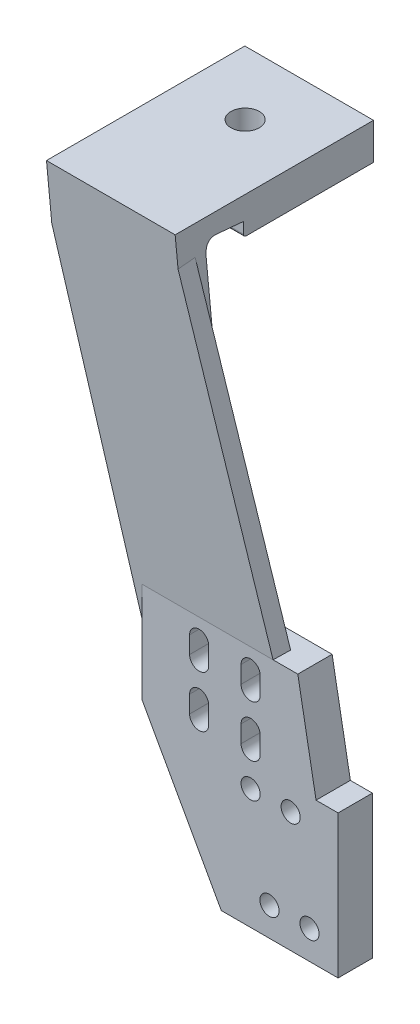
SolidWorks part; units mm, degrees
ref_plane "Front Plane" through (0, 0, 0) normal (0, 0, 1) x (1, 0, 0)
ref_plane "Top Plane" through (0, 0, 0) normal (0, 1, 0) x (1, 0, 0)
ref_plane "Right Plane" through (0, 0, 0) normal (1, 0, 0) x (0, 0, -1)
sketch "Sketch1" plane through (0, 0, 0) normal (0, 0, 1) x (1, 0, 0)
  line L0 (0, 0) -> (-40.8425, 0)
  line L5 (0, 85) -> (0, 0)
  line L6 (-40.8425, 0) -> (-68.59, 50)
  line L7 (-68.59, 50) -> (-68.59, 85)
  line L8 (-68.59, 85) -> (0, 85)
  line L9 (-30.59, 57) -> (-48.59, 57) construction
  line L10 (-48.59, 57) -> (-48.59, 75) construction
  line L11 (-48.59, 75) -> (-30.59, 75) construction
  line L12 (-30.59, 75) -> (-30.59, 57) construction
  line L13 (-30.59, 57) -> (-30.59, 42) construction
  line L14 (-30.59, 42) -> (-16.59, 42) construction
  line L15 (-16.59, 42) -> (-10, 10) construction
  line L16 (-10, 10) -> (-24, 10) construction
  line L17 (-24, 10) -> (-30.59, 42) construction
  line L18 (-48.59, 60) -> (-48.59, 54) construction
  line L19 (-45.24, 60) -> (-45.24, 54)
  line L20 (-51.94, 60) -> (-51.94, 54)
  line L21 (-48.59, 78) -> (-48.59, 72) construction
  line L22 (-45.24, 78) -> (-45.24, 72)
  line L23 (-51.94, 78) -> (-51.94, 72)
  line L24 (-30.59, 78) -> (-30.59, 72) construction
  line L25 (-27.24, 78) -> (-27.24, 72)
  line L26 (-33.94, 78) -> (-33.94, 72)
  line L27 (-30.59, 60) -> (-30.59, 54) construction
  line L28 (-27.24, 60) -> (-27.24, 54)
  line L29 (-33.94, 60) -> (-33.94, 54)
  line L30 (-33.94, 72) -> (-33.94, 60) construction
  line L31 (-30.59, 60) -> (-48.59, 60) construction
  line L32 (-45.24, 72) -> (-45.24, 60) construction
  line L33 (-48.59, 63.35) -> (-30.59, 63.35) construction
  line L34 (-48.59, 68.65) -> (-30.59, 68.65) construction
  circle A0 centre (-30.59, 42) radius 3.35
  circle A1 centre (-16.59, 42) radius 3.35
  circle A2 centre (-24, 10) radius 3.35
  circle A3 centre (-10, 10) radius 3.35
  arc A4 (-45.24, 60) -> (-51.94, 60) centre (-48.59, 60) ccw
  arc A5 (-51.94, 54) -> (-45.24, 54) centre (-48.59, 54) ccw
  arc A6 (-45.24, 78) -> (-51.94, 78) centre (-48.59, 78) ccw
  arc A7 (-51.94, 72) -> (-45.24, 72) centre (-48.59, 72) ccw
  arc A8 (-27.24, 78) -> (-33.94, 78) centre (-30.59, 78) ccw
  arc A9 (-33.94, 72) -> (-27.24, 72) centre (-30.59, 72) ccw
  arc A10 (-27.24, 60) -> (-33.94, 60) centre (-30.59, 60) ccw
  arc A11 (-33.94, 54) -> (-27.24, 54) centre (-30.59, 54) ccw
  point P20 (-48.59, 57)
  point P26 (-48.59, 75)
  point P33 (-30.59, 75)
  point P40 (-30.59, 57)
  point P54 (-78.59, 26.8043)
  point P57 (0, 0)
  point P58 (-78.59, 29.2773)
  point P59 (-63.59, 50.341)
  dimension "D10" = 6.7
  dimension "D11" = 6.7
  dimension "D12" = 6.7
  dimension "D13" = 6.7
  dimension "D14" = 3.35
  dimension "D15" = 6
  dimension "D16" = 6
  dimension "D17" = 20
  dimension "D1" = 18
  dimension "D2" = 18
  dimension "D3" = 15
  dimension "D4" = 32
  dimension "D5" = 14
  dimension "D6" = 6.59
  dimension "D7" = 10
  dimension "D8" = 10
  dimension "D9" = 85
  dimension "D18" = 50
extrude "Boss-Extrude1" add sketch "Sketch1" along normal blind 12
sketch "Sketch4" plane through (-68.59, 0, 0) normal (-1, 0, 0) x (0, 0, 1)
  line L0 (11.2201, 191.4749) -> (11.5777, 192.6361) construction
  line L1 (12.1758, 191.1806) -> (12.5792, 192.4904) construction
  line L2 (11.847, 188.2578) -> (5.8724, 123.7613) construction
  line L3 (12.5541, 195.0368) -> (12.5465, 195.8087) construction
  line L4 (12.5541, 195.0368) -> (12.5246, 198.0227) construction
  line L5 (1.3504, 200.2894) -> (-0.4753, 200.0947)
  line L6 (3.8584, 112.8614) -> (0, 71.2101) construction
  line L7 (10.8512, 188.3501) -> (4.8766, 123.8536) construction
  line L9 (0, 85) -> (0, 50) construction
  line L10 (5.8724, 123.7613) -> (2.2817, 85)
  line L11 (0, 85) -> (0, 71.2101) construction
  line L20 (12.5465, 195.8087) -> (5.8724, 123.7613)
  line L21 (4.8541, 112.7691) -> (0, 60.3688) construction
  line L22 (-0.4753, 200.0947) -> (-0.4753, 198.17)
  line L23 (-45.9753, 195.2536) -> (-45.9753, 208.0041)
  line L24 (-45.9753, 208.0041) -> (23.3945, 208.0041)
  line L25 (23.3945, 208.0041) -> (12, 85)
  line L26 (12, 85) -> (12, 50) construction
  line L27 (12, 85) -> (2.2817, 85)
  line L28 (9.3505, 199.9855) -> (1.4375, 199.2932) construction
  line L29 (11.5541, 195.027) -> (11.5247, 198.0128) construction
  line L30 (11.5777, 192.6361) -> (11.5541, 195.027) construction
  line L31 (-30.5003, 194.2536) -> (-16.9503, 194.2536) construction
  line L32 (-45.9753, 194.2536) -> (-1.4753, 194.2536) construction
  line L33 (0.5247, 198.17) -> (0.5247, 196.2536) construction
  line L34 (-0.4753, 198.17) -> (-0.4753, 196.2536)
  line L35 (-45.9753, 195.2536) -> (-1.4753, 195.2536)
  line L36 (2.2817, 85) -> (0, 60.3688) construction
  line L37 (12.5465, 195.8087) -> (12.5246, 198.0227)
  line L38 (9.2633, 200.9817) -> (1.3504, 200.2894)
  line L39 (12.5792, 192.4904) -> (12.5541, 195.0368) construction
  line L40 (0, 71.2101) -> (0, 60.3688) construction
  line L41 (0, 60.3688) -> (0, 50) construction
  line L42 (0, 71.2101) -> (-0.9957, 60.461) construction
  line L43 (3.8584, 112.8614) -> (-0.9957, 60.461) construction
  spline S5 degree 3 poles (9.3505, 199.9855) (10.5905, 200.094) (11.5124, 199.2576) (11.5247, 198.0128) knots 0 0 0 0 1 1 1 1 weights 1 0.786145 0.786145 1 construction
  spline S6 degree 3 poles (11.2201, 191.4749) (11.3469, 191.6574) (11.435, 191.8468) (11.5226, 192.1387) (11.5442, 192.2377) (11.5722, 192.4366) (11.5787, 192.5373) (11.5777, 192.6361) knots 0 0 0 0 0.5 0.5 0.75 0.75 1 1 1 1 construction
  spline S7 degree 3 poles (11.2201, 191.4749) (11.1122, 191.3196) (10.9929, 191.1932) (10.7375, 190.9784) (10.6, 190.89) (10.1735, 190.681) (9.8712, 190.6116) (9.5474, 190.6166) knots 0 0 0 0 0.25 0.25 0.5 0.5 1 1 1 1 construction
  spline S8 degree 3 poles (0.5247, 196.2536) (0.5247, 195.082) (-0.3038, 194.2536) (-1.4753, 194.2536) knots 0 0 0 0 1 1 1 1 weights 1 0.804738 0.804738 1 construction
  spline S9 degree 3 poles (0.5247, 198.297) (0.5247, 198.843) (0.8936, 199.2456) (1.4375, 199.2932) knots 0 0 0 0 1 1 1 1 weights 1 0.824852 0.824852 1 construction
  spline S10 degree 1 poles (-0.4753, 196.2536) (-1.4753, 195.2536) knots 0 0 1 1 construction
  spline S11 degree 3 poles (-0.4753, 196.2536) (-0.4753, 196.1287) (-0.5183, 195.8844) (-0.7462, 195.5245) (-1.1062, 195.2966) (-1.3504, 195.2536) (-1.4753, 195.2536) knots 0 0 0 0 0.25 0.5 0.75 1 1 1 1
  spline S13 degree 1 poles (9.2633, 200.9817) (12.5246, 198.0227) knots 0 0 1 1 construction
  spline S15 degree 3 poles (12.5246, 198.0227) (12.5228, 198.213) (12.4851, 198.5848) (12.2469, 199.3733) (11.6072, 200.2883) (10.6345, 200.8363) (9.8266, 200.9968) (9.4529, 200.9983) (9.2633, 200.9817) knots 0 0 0 0 0.125 0.25 0.5 0.75 0.875 1 1 1 1
  dimension "D1" = 1
  dimension "D4" = 12.7505
  dimension "D5" = 45.5
  dimension "D2" = 1
  dimension "D3" = 1
extrude "Boss-Extrude4" add sketch "Sketch4" against normal blind 23
sketch "Sketch6" plane through (0, 0, 12) normal (0, 0, 1) x (1, 0, 0)
  line L1 (33.593, 50) -> (-42.0441, 50) construction
  line L3 (-66.4213, 50.1) -> (-8.9266, 50.1) construction
  line L4 (-16.7816, 99.7606) -> (-7.7092, 50)
  line L5 (-7.7092, 50) -> (7.4283, 50)
  line L6 (7.4283, 50) -> (-1.6441, 99.7606)
  line L7 (-1.6441, 99.7606) -> (-16.7816, 99.7606)
  spline S1 degree 3 poles (-10.4712, 64.3102) (-10.7633, 65.9972) (-11.3896, 69.5988) (-12.2266, 74.368) (-12.8564, 77.9308) (-13.3338, 80.6215) (-13.6538, 82.4188) (-13.9333, 83.9843) (-14.2262, 85.6229) (-14.5696, 87.5385) (-15.0022, 89.9437) (-15.2788, 91.4774) (-15.5371, 92.9071) (-15.7443, 94.0521) (-16.0696, 95.8471) (-16.391, 97.6166) (-16.6547, 99.0647) (-16.8188, 99.9649) (-16.9749, 100.8207) (-17.1882, 101.9882) (-17.3914, 103.0993) (-17.5827, 104.1439) (-17.7497, 105.0548) (-17.9137, 105.9489) (-18.0988, 106.9568) (-18.3283, 108.2048) (-18.5633, 109.4812) (-18.8151, 110.8471) (-18.9713, 111.6937) (-19.0726, 112.2418) (-19.0784, 112.2735) knots 0 0 0 0 0.105156 0.224601 0.297666 0.327685 0.392722 0.410003 0.425561 0.495178 0.529805 0.576042 0.591158 0.619292 0.647717 0.703538 0.730105 0.738424 0.759931 0.783716 0.811579 0.829551 0.849183 0.868669 0.8856 0.912362 0.946905 0.96563 0.998009 1 1 1 1 construction
  point P10 (7.4283, 50)
  dimension "D1" = 34.3349
  dimension "D2" = 14.892
extrude "Cut-Extrude2" cut sketch "Sketch6" against normal through all
sketch "Sketch7" plane through (-68.59, 0, 0) normal (-1, 0, 0) x (0, 0, 1)
  line L0 (1.3504, 200.2894) -> (9.2633, 200.9817) construction
  line L1 (-0.4753, 200.0947) -> (1.3504, 200.2894) construction
  line L2 (-0.4753, 196.2536) -> (-0.4753, 200.0947) construction
  line L3 (-45.9753, 195.2536) -> (-1.4753, 195.2536) construction
  line L4 (23.3945, 208.0041) -> (-45.9753, 208.0041) construction
  line L5 (-45.9753, 208.0041) -> (-45.9753, 195.2536) construction
  line L6 (1.3504, 200.2894) -> (9.2633, 200.9817)
  line L7 (-0.4753, 200.0947) -> (1.3504, 200.2894)
  line L8 (-0.4753, 196.2536) -> (-0.4753, 200.0947)
  line L9 (-45.9753, 195.2536) -> (-1.4753, 195.2536)
  line L10 (23.3945, 208.0041) -> (-45.9753, 208.0041)
  line L11 (-45.9753, 208.0041) -> (-45.9753, 195.2536)
  line L12 (12.5246, 198.0227) -> (12.5465, 195.8087) construction
  line L13 (12.5246, 198.0227) -> (12.5465, 195.8087)
  line L14 (23.3945, 208.0041) -> (21.5497, 188.0894)
  line L15 (12, 85) -> (23.3945, 208.0041) construction
  line L16 (21.5497, 188.0894) -> (11.9141, 188.982)
  line L17 (12.5465, 195.8087) -> (2.2817, 85) construction
  line L18 (11.9141, 188.982) -> (12.5465, 195.8087)
  spline S0 degree 3 poles (-5906.1312, 1191.5812) (30.2885, 66.2783) (-6.8837, 204.3169) (10.6345, 200.8363) (11.6072, 200.2883) (12.2469, 199.3733) (17.41, 182.2752) (-123.5834, 205.8861) (1572.1121, -5593.4687) knots -10.341725 -10.341725 -10.341725 -10.341725 0.125 0.25 0.5 0.75 0.875 11.341749 11.341749 11.341749 11.341749 only from (9.2633, 200.9817) to (12.5246, 198.0227) construction
  spline S1 degree 3 poles (-2005.4095, -5457.3863) (-38.0178, 481.1429) (-13.4912, 187.454) (-0.7462, 195.5245) (7.3244, 208.2696) (-286.3713, 232.7966) (5652.3672, 2200.2549) knots -25.8065 -25.8065 -25.8065 -25.8065 0.25 0.5 0.75 26.806797 26.806797 26.806797 26.806797 only from (-1.4753, 195.2536) to (-0.4753, 196.2536) construction
  spline S2 degree 3 poles (9.2633, 200.9817) (9.4529, 200.9983) (9.8266, 200.9968) (10.6345, 200.8363) (11.6072, 200.2883) (12.2469, 199.3733) (12.4851, 198.5848) (12.5228, 198.213) (12.5246, 198.0227) knots 0 0 0 0 0.125 0.25 0.5 0.75 0.875 1 1 1 1
  spline S3 degree 3 poles (-1.4753, 195.2536) (-1.3504, 195.2536) (-1.1062, 195.2966) (-0.7462, 195.5245) (-0.5183, 195.8844) (-0.4753, 196.1287) (-0.4753, 196.2536) knots 0 0 0 0 0.25 0.5 0.75 1 1 1 1
  point P9 (21.542, 188.0068)
  point P18 (11.3096, 182.4571)
  dimension "D1" = 20
extrude "Boss-Extrude5" add sketch "Sketch7" along normal blind 22
sketch "Sketch9" plane through (0, -0.379, 4.0909) normal (0, -0.0922, 0.9957) x (1, 0, 0)
  line L0 (-90.59, 189.2753) -> (-68.59, 68.3191)
  line L3 (-68.59, 85.7445) -> (-68.59, 50.8937) construction
  point P2 (-68.59, 50.3403)
  point P3 (-68.59, 68.3191)
  point P4 (-72.4788, 57.8714)
  point P6 (-68.59, 50.3403)
rib "Rib8" sketch "Sketch9" sketch "Sketch9" thickness 8 extrusion direction parallel to sketch draft on no parameters "D1"=8
sketch "Sketch10" plane through (0, -0.379, 4.0909) normal (0, -0.0922, 0.9957) x (1, 0, 0)
  line L0 (-45.59, 198.3338) -> (-22.7427, 85.7445)
  line L1 (-45.59, 85.7445) -> (-45.59, 209.2753) construction
  line L2 (-14.0904, 85.7445) -> (-45.59, 85.7445) construction
  point P6 (-45.59, 198.3338)
  point P7 (-22.7427, 85.7445)
rib "Rib13" sketch "Sketch10" sketch "Sketch10" thickness 6 extrusion direction parallel to sketch draft on no parameters "D1"=6
hole_wizard "25/64 (0.39063) Diameter Hole1" positions "Sketch13" profile "Sketch12" hole size "25/64" standard "ANSI Inch" end condition through all
sketch "Sketch13" plane through (0, 208.0041, 0) normal (0, 1, 0) x (1, 0, 0)
  line L4 (-90.4921, 1.4753) -> (-45.9921, 1.4753) construction
  line L5 (-45.9921, 1.4753) -> (-45.9921, 45.9753) construction
  line L6 (-45.9921, 45.9753) -> (-90.4921, 45.9753) construction
  line L7 (-90.4921, 45.9753) -> (-90.4921, 1.4753) construction
  line L8 (-90.4921, 1.4753) -> (-45.9921, 45.9753) construction
  line L9 (-45.9921, 45.9753) -> (-90.4921, 45.9753) construction
  line L10 (-90.4921, 45.9753) -> (-45.9921, 1.4753) construction
  spline S1 degree 3 poles (-68.2421, 28.5003) (-77.7921, 28.5003) (-77.7921, 18.9503) (-68.2421, 18.9503) (-58.6921, 18.9503) (-58.6921, 28.5003) (-68.2421, 28.5003) (-77.7921, 28.5003) (-77.7921, 18.9503) knots -0.5 0 0 0 0.5 0.5 0.5 1 1 1 1.5 1.5 1.5 weights 1 0.333333 0.333333 1 0.333333 0.333333 1 0.333333 0.333333 only from (-68.2421, 28.5003) to (-68.2421, 28.5003) construction
  spline S3 degree 3 poles (-68.2421, 30.5003) (-81.7921, 30.5003) (-81.7921, 16.9503) (-68.2421, 16.9503) (-54.6921, 16.9503) (-54.6921, 30.5003) (-68.2421, 30.5003) (-81.7921, 30.5003) (-81.7921, 16.9503) knots -0.5 0 0 0 0.5 0.5 0.5 1 1 1 1.5 1.5 1.5 weights 1 0.333333 0.333333 1 0.333333 0.333333 1 0.333333 0.333333 only from (-68.2421, 30.5003) to (-68.2421, 30.5003) construction
  point P0 (-68.2421, 23.7253)
sketch "Sketch12" plane through (-68.2421, 208.0041, -23.7253) normal (1, 0, 0) x (0, 0, 1)
  line L0 (0, 0) -> (0, 208.0041)
  line L1 (0, 208.0041) -> (4.961, 208.0041)
  line L2 (4.961, 208.0041) -> (4.961, 0)
  line L5 (4.961, 0) -> (0, 0)
  line L11 (0, -6.35) -> (0, 107.95) construction
  dimension "Thru Hole Dia." = 9.922
  dimension "Thru Hole Depth" = 208.0041
